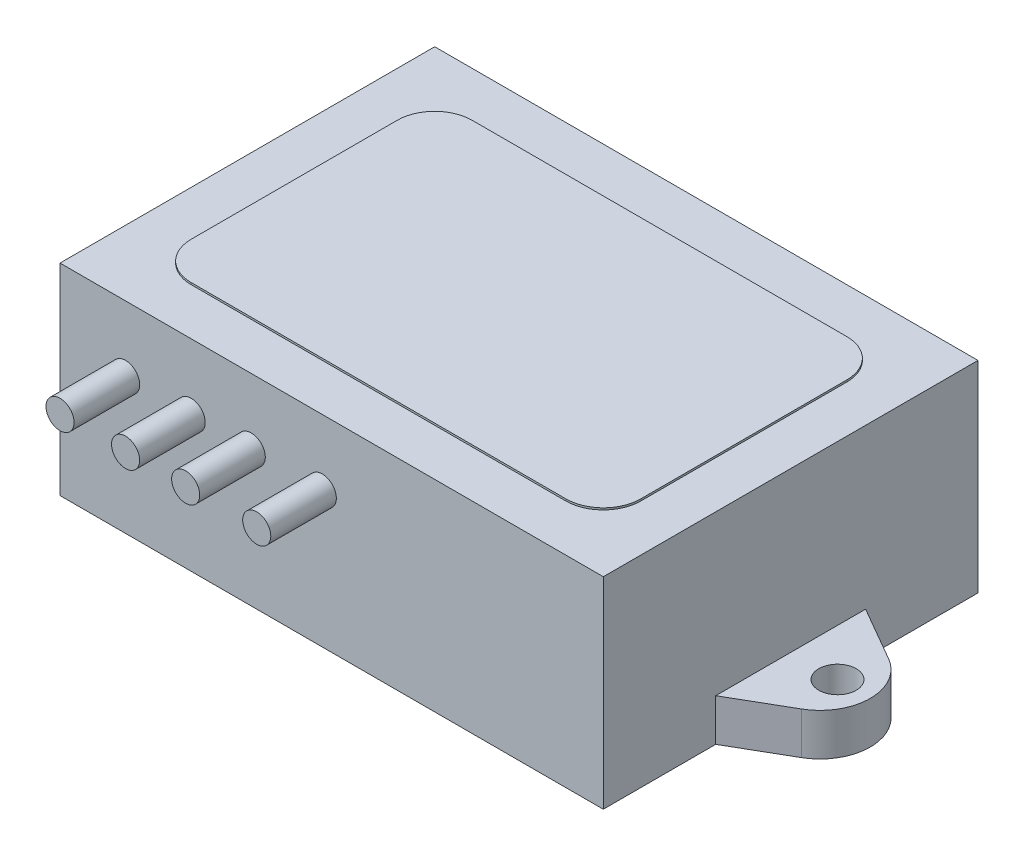
SolidWorks part; units mm, degrees
ref_plane "Front Plane" through (0, 0, 0) normal (0, 0, 1) x (1, 0, 0)
ref_plane "Top Plane" through (0, 0, 0) normal (0, 1, 0) x (1, 0, 0)
ref_plane "Right Plane" through (0, 0, 0) normal (1, 0, 0) x (0, 0, -1)
sketch "Sketch1" plane through (0, 0, 0) normal (0, 1, 0) x (1, 0, 0)
  line L1 (0, 0) -> (58, 0)
  line L2 (0, 0) -> (0, 40)
  line L3 (0, 40) -> (58, 40)
  line L4 (58, 0) -> (58, 40)
  dimension "D1" = 58
  dimension "D2" = 40
extrude "Boss-Extrude1" add sketch "Sketch1" along normal blind 21.5
sketch "Sketch2" plane through (0, 0, 0) normal (0, 1, 0) x (1, 0, 0)
  line L0 (29, 40) -> (29, 0) construction
  line L1 (58, 40) -> (0, 40) construction
  line L2 (0, 0) -> (58, 0) construction
  line L3 (0, 28) -> (0, 12)
  line L4 (0, 40) -> (0, 0) construction
  line L5 (0, 20) -> (-8.5, 20) construction
  line L8 (58, 20) -> (66.5, 20) construction
  line L9 (58, 28) -> (63.8218, 24.6388)
  line L10 (58, 12) -> (63.8218, 15.3612)
  line L11 (58, 28) -> (58, 12)
  line L12 (0, 12) -> (-5.8218, 15.3612)
  line L13 (0, 28) -> (-5.8218, 24.6388)
  arc A0 (-5.8218, 15.3612) -> (-5.8218, 24.6388) centre (-3.1436, 20) cw
  arc A1 (63.8218, 15.3612) -> (63.8218, 24.6388) centre (61.1436, 20) ccw
  point P10 (0, 20)
  point P11 (29, 20)
  dimension "D1" = 16
  dimension "D2" = 8.5
  dimension "D3" = 120
extrude "Boss-Extrude2" add sketch "Sketch2" along normal blind 4.5
sketch "Sketch3" plane through (0, 4.5, 0) normal (0, 1, 0) x (1, 0, 0)
  line L0 (29, 40) -> (29, 0) construction
  line L1 (58, 40) -> (0, 40) construction
  line L2 (0, 0) -> (58, 0) construction
  line L3 (-8.5, 20) -> (29, 20) construction
  arc A0 (-5.8218, 24.6388) -> (-5.8218, 15.3612) centre (-3.1436, 20) ccw construction
  circle A1 centre (-5, 20) radius 2
  circle A2 centre (63, 20) radius 2
  dimension "D2" = 4
  dimension "D1" = 3.5
extrude "Cut-Extrude1" cut sketch "Sketch3" against normal through all
sketch "Sketch4" plane through (0, 21.5, 0) normal (0, 1, 0) x (1, 0, 0)
  line L4 (5, 35) -> (5, 5)
  line L5 (5, 5) -> (53, 5)
  line L6 (53, 5) -> (53, 35)
  line L7 (53, 35) -> (5, 35)
  line L8 (5, 31) -> (5, 9)
  line L9 (9, 5) -> (49, 5)
  line L10 (53, 9) -> (53, 31)
  line L11 (49, 35) -> (9, 35)
  arc A0 (5, 9) -> (9, 5) centre (9, 9) ccw
  arc A1 (49, 5) -> (53, 9) centre (49, 9) ccw
  arc A2 (53, 31) -> (49, 35) centre (49, 31) ccw
  arc A3 (5, 31) -> (9, 35) centre (9, 31) cw
  dimension "D2" = 4
  dimension "D1" = 5
extrude "Boss-Extrude3" add sketch "Sketch4" along normal blind 0.2
sketch "Sketch5" plane through (0, 21.7, 0) normal (0, 1, 0) x (1, 0, 0)
  text T0 "MPPT Solar\r\nCharge Controller"
sketch "Sketch6" plane through (0, 0, 0) normal (0, 0, 1) x (1, 0, 0)
  line L0 (0, 21.5) -> (58, 21.5) construction
  line L1 (0, 21.5) -> (0, 0) construction
  circle A0 centre (7, 14.5) radius 1.5
  dimension "D3" = 3
  dimension "D1" = 7
  dimension "D2" = 7
sketch "Sketch8" plane through (0, 0, 0) normal (0, 0, 1) x (1, 0, 0)
  circle A0 centre (14, 14.5) radius 1.5
  circle A1 centre (28, 14.5) radius 1.5
  circle A2 centre (7, 14.5) radius 1.5 construction
  dimension "D1" = 7
  dimension "D2" = 14
sketch "Sketch9" plane through (0, 0, 0) normal (0, 0, 1) x (1, 0, 0)
  circle A0 centre (20.4127, 14.5) radius 1.5
  circle A1 centre (7, 14.5) radius 1.5 construction
extrude "Boss-Extrude4" add sketch "Sketch6" along normal blind 7
extrude "Boss-Extrude6" add sketch "Sketch8" along normal blind 7
extrude "Boss-Extrude7" add sketch "Sketch9" along normal blind 7
